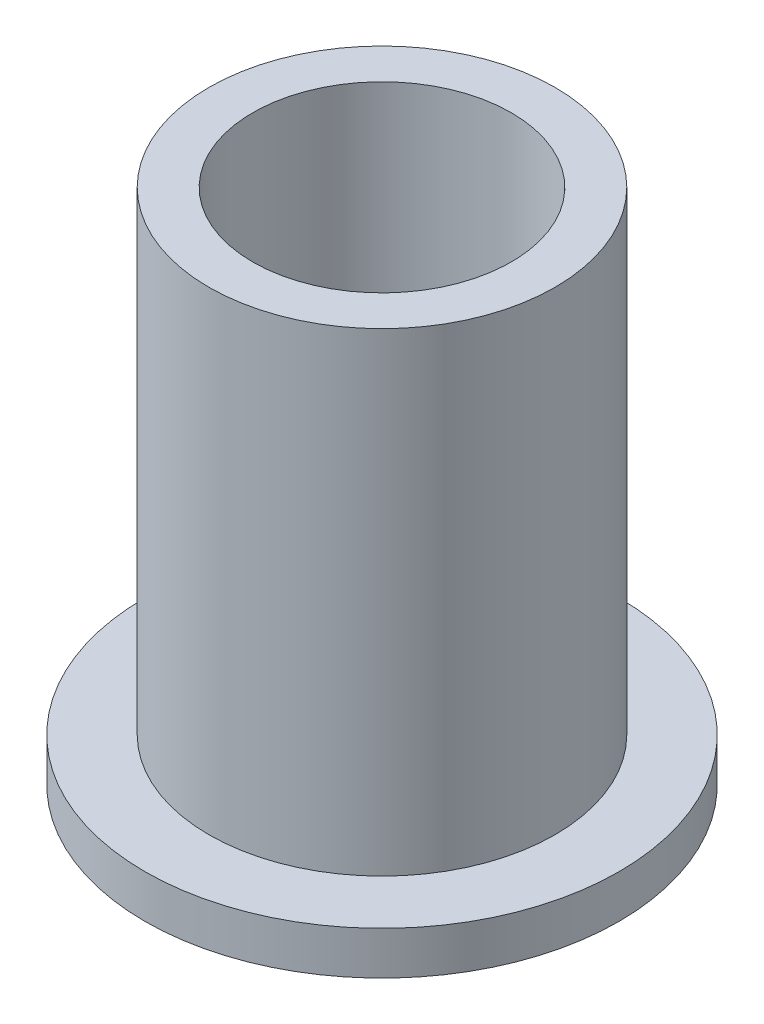
SolidWorks part; units mm, degrees
ref_plane "Front" through (0, 0, 0) normal (0, 0, 1) x (1, 0, 0)
ref_plane "Top" through (0, 0, 0) normal (0, 1, 0) x (1, 0, 0)
ref_plane "Right" through (0, 0, 0) normal (1, 0, 0) x (0, 0, -1)
sketch "Sketch1" plane through (0, 0, 0) normal (0, 1, 0) x (1, 0, 0)
  circle A0 centre (0, 0) radius 4.7625
  circle A1 centre (0, 0) radius 6.3754
  circle A2 centre (0, 0) radius 8.7312
  dimension "ID" = 9.525
  dimension "OD" = 12.7508
  dimension "FlangeOD" = 17.4625
sketch "Sketch2" plane through (0, 0, 0) normal (0, 1, 0) x (1, 0, 0)
  circle A0 centre (0, 0) radius 4.7625 construction
  circle A1 centre (0, 0) radius 6.3754 construction
  circle A2 centre (0, 0) radius 4.7625
  circle A3 centre (0, 0) radius 6.3754
extrude "Boss-Extrude1" add sketch "Sketch2" along normal blind 19.05
sketch "Sketch3" plane through (0, 0, 0) normal (0, 1, 0) x (1, 0, 0)
  circle A0 centre (0, 0) radius 8.7312 construction
  circle A1 centre (0, 0) radius 6.3754 construction
  circle A2 centre (0, 0) radius 8.7312
  circle A3 centre (0, 0) radius 6.3754
extrude "Boss-Extrude2" add sketch "Sketch3" along normal blind 1.5875
